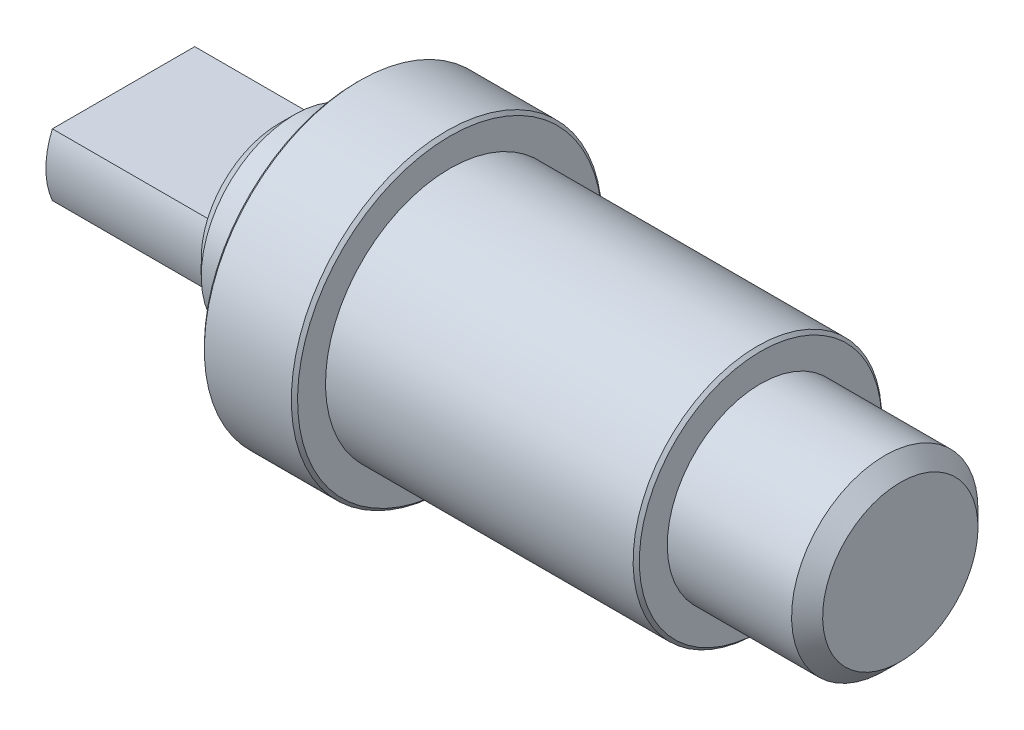
SolidWorks part; units mm, degrees
ref_plane "前视基准面" through (0, 0, 0) normal (0, 0, 1) x (1, 0, 0)
ref_plane "上视基准面" through (0, 0, 0) normal (0, 1, 0) x (1, 0, 0)
ref_plane "右视基准面" through (0, 0, 0) normal (1, 0, 0) x (0, 0, -1)
sketch "草图1" plane through (0, 0, 0) normal (0, 0, 1) x (1, 0, 0)
  line L0 (0, 0) -> (0, 2.5)
  line L1 (19.5, 3) -> (15.5, 3)
  line L2 (20, 2.5) -> (20, 0)
  line L3 (20, 0) -> (0, 0)
  line L4 (0, 0) -> (0.0322, -0.0774)
  line L5 (15.5, 3) -> (15.5, 3.9)
  line L6 (15.4, 4) -> (5.5, 4)
  line L7 (5.5, 4) -> (5.5, 4.9)
  line L8 (5.4, 5) -> (2.6, 5)
  line L9 (2.5, 4.9) -> (2.5, 3)
  line L10 (2.5, 3) -> (0.5, 3)
  line L11 (0.5, 3) -> (0, 2.5)
  line L12 (19.5, 3) -> (20, 2.5)
  line L13 (2.6, 5) -> (2.5, 4.9)
  line L14 (5.5, 4.9) -> (5.4, 5)
  line L15 (15.5, 3.9) -> (15.4, 4)
  point P4 (15.5, 4)
  point P7 (0, 3)
  point P8 (20, 3)
  point P10 (5.5, 5)
  point P11 (2.5, 5)
revolve "旋转1" add sketch "草图1" angle 360 about L3
sketch "草图4" plane through (0, 0, 0) normal (1, 0, 0) x (0, 0, -1)
  line L1 (0, 1) -> (2.2913, 1)
  line L2 (0, 1) -> (-2.2913, 1)
  line L4 (0, -1) -> (2.2913, -1)
  line L5 (0, -1) -> (-2.2913, -1)
  circle A0 centre (0, 0) radius 2.5 construction
  arc A1 (-2.2913, 1) -> (-2.2913, -1) centre (0, 0) ccw
  arc A2 (2.2913, -1) -> (2.2913, 1) centre (0, 0) ccw
extrude "凸台-拉伸3" add sketch "草图4" against normal blind 5
